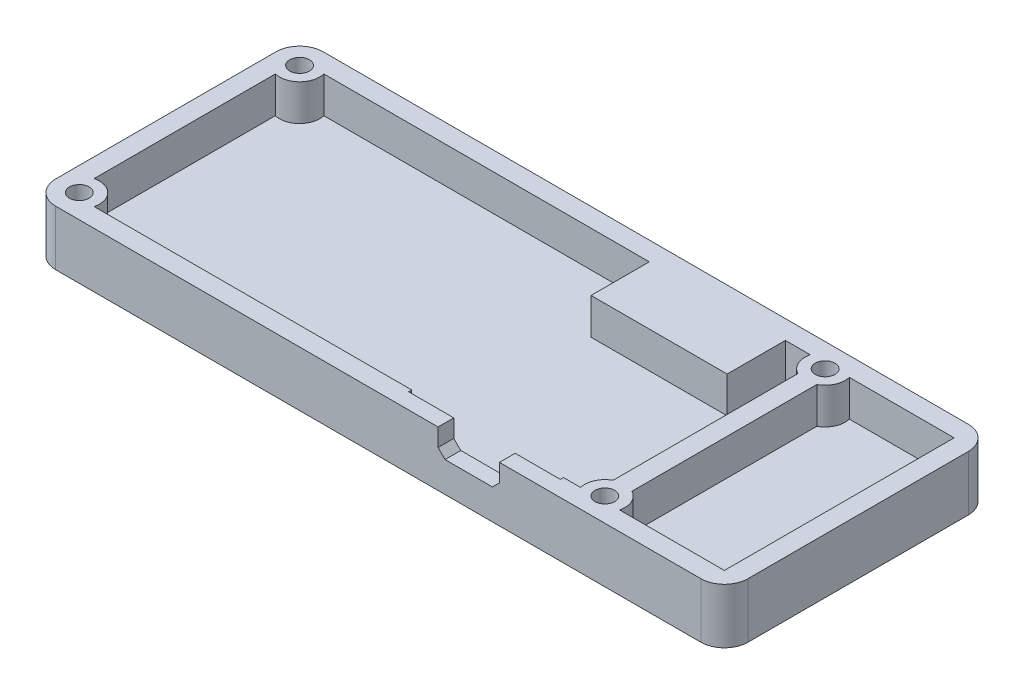
SolidWorks part; units mm, degrees
ref_plane "Front Plane" through (0, 0, 0) normal (0, 0, 1) x (1, 0, 0)
ref_plane "Top Plane" through (0, 0, 0) normal (0, 1, 0) x (1, 0, 0)
ref_plane "Right Plane" through (0, 0, 0) normal (1, 0, 0) x (0, 0, -1)
sketch "Sketch1" plane through (0, 0, 0) normal (0, 1, 0) x (1, 0, 0)
  line L1 (-35.5, 17) -> (35.5, 17)
  line L2 (-35.5, 17) -> (-35.5, -17)
  line L3 (-35.5, -17) -> (35.5, -17)
  line L4 (35.5, 17) -> (35.5, -17)
  line L5 (-35.5, 17) -> (35.5, -17) construction
  line L6 (-35.5, -17) -> (35.5, 17) construction
  point P0 (0, 0)
  dimension "D1" = 34
  dimension "D2" = 71
extrude "Boss-Extrude1" add sketch "Sketch1" along normal blind 7
shell "Shell1" thickness 2.4
sketch "Sketch3" plane through (0, 0, 0) normal (0, -1, 0) x (1, 0, 0)
  line L0 (35.5, 17) -> (35.5, -17) construction
  line L1 (35.5, 17) -> (52.5, 17)
  line L2 (35.5, 17) -> (35.5, -17)
  line L3 (35.5, -17) -> (52.5, -17)
  line L4 (52.5, 17) -> (52.5, -17)
  line L6 (-35.5, 17) -> (35.5, 17) construction
  line L7 (35.5, -17) -> (-35.5, -17) construction
  dimension "D1" = 17
extrude "Boss-Extrude2" add sketch "Sketch3" against normal up to surface (7 mm away) up to face at (0, 7, 0)
sketch "Sketch4" plane through (0, 7, 0) normal (0, 1, 0) x (1, 0, 0)
  line L3 (35.5, -14.6) -> (50.1, -14.6)
  line L8 (35.5, -14.6) -> (35.5, 14.6)
  line L9 (35.5, 14.6) -> (50.1, 14.6)
  line L10 (50.1, -14.6) -> (50.1, 14.6)
  line L11 (33.1, -14.6) -> (33.1, 14.6) construction
  line L12 (52.5, 17) -> (52.5, -17) construction
  line L13 (52.5, 17) -> (-35.5, 17) construction
  line L14 (-35.5, -17) -> (52.5, -17) construction
  dimension "D1" = 2.4
  dimension "D2" = 2.4
  dimension "D3" = 2.4
  dimension "D4" = 2.4
extrude "Cut-Extrude2" cut sketch "Sketch4" against normal offset from surface (4.6 mm away) 2.4 up to face at (8.5, 0, 0)
sketch "Sketch5" plane through (0, 7, 0) normal (0, 1, 0) x (1, 0, 0)
  line L0 (-33.1, -14.6) -> (33.1, -14.6) construction
  line L1 (29.65, -15) -> (10.35, -15)
  line L2 (29.65, -15) -> (29.65, -14.6)
  line L3 (29.65, -14.6) -> (10.35, -14.6)
  line L4 (10.35, -15) -> (10.35, -14.6)
  line L5 (28.65, -15) -> (28.65, 12.9) construction
  line L6 (11.35, -15) -> (11.35, 12.9) construction
  dimension "D1" = 1
  dimension "D2" = 1
  dimension "D3" = 0.4
extrude "Cut-Extrude3" cut sketch "Sketch5" against normal up to surface (4.6 mm away) up to face at (0, 2.4, 0)
sketch "Sketch6" plane through (0, 0, 17) normal (0, 0, 1) x (1, 0, 0)
  line L30 (16.1, 4.7379) -> (16.9879, 3.85)
  line L31 (16.9879, 3.85) -> (23.0121, 3.85)
  line L32 (23.0121, 3.85) -> (23.9, 4.7379)
  line L33 (23.9, 4.7379) -> (23.9, 6.3)
  line L34 (23.25, 6.95) -> (16.75, 6.95)
  line L35 (16.1, 6.3) -> (16.1, 4.7379)
  line L36 (16.1, 4.7379) -> (16.9879, 3.85)
  line L37 (16.9879, 3.85) -> (23.0121, 3.85)
  line L38 (23.0121, 3.85) -> (23.9, 4.7379)
  line L39 (23.9, 4.7379) -> (23.9, 6.3)
  line L41 (16.1, 6.3) -> (16.1, 4.7379)
  line L42 (23.9, 6.3) -> (23.9, 7)
  line L43 (-35.5, 7) -> (52.5, 7) construction
  line L44 (23.9, 7) -> (16.1, 7)
  line L45 (16.1, 7) -> (16.1, 6.3)
  arc A14 (23.9, 6.3) -> (23.25, 6.95) centre (23.25, 6.3) ccw
  arc A15 (16.75, 6.95) -> (16.1, 6.3) centre (16.75, 6.3) ccw
  dimension "D1" = 0.15
extrude "Cut-Extrude4" cut sketch "Sketch6" against normal up to surface (2 mm away) up to face at (20, 4.7, 15)
sketch "Sketch7" plane through (0, 2.4, 0) normal (0, 1, 0) x (1, 0, 0)
  line L0 (33.1, 14.6) -> (-33.1, 14.6) construction
  line L1 (28.65, 14.6) -> (11.35, 14.6)
  line L2 (28.65, 14.6) -> (28.65, 7.2)
  line L3 (28.65, 7.2) -> (11.35, 7.2)
  line L4 (11.35, 14.6) -> (11.35, 7.2)
  line L6 (28.65, -15) -> (28.65, 12.9) construction
  line L7 (11.35, -15) -> (11.35, 12.9) construction
  line L8 (29.65, -15) -> (10.35, -15) construction
  dimension "D1" = 22.2
extrude "Boss-Extrude3" add sketch "Sketch7" along normal up to surface (4.6 mm away) up to face at (12.125, 7, 7.7)
fillet "Fillet1" radius 3 4 edges at (52.5, 3.5, 17) (52.5, 3.5, -17) (-35.5, 3.5, -17) (-35.5, 3.5, 17)
sketch "Sketch8" plane through (0, 0, 0) normal (0, -1, 0) x (-1, 0, 0)
  circle A0 centre (32.5, 14) radius 2.5547
  circle A1 centre (32.5, -14) radius 2.5547
  circle A2 centre (-34.3, 14) radius 2.5547
  circle A3 centre (-34.3, -14) radius 2.5547
  arc A4 (-35.5, -11.7447) -> (-36.7832, -14.6) centre (-34.3, -14) ccw construction
  arc A5 (-36.7832, 14.6) -> (-35.5, 11.7447) centre (-34.3, 14) ccw construction
  arc A6 (33.1, -11.5168) -> (30.0168, -14.6) centre (32.5, -14) ccw construction
  arc A7 (30.0168, 14.6) -> (33.1, 11.5168) centre (32.5, 14) ccw construction
extrude "Boss-Extrude4" add sketch "Sketch8" against normal up to vertex (7 mm away)
sketch "Sketch9" plane through (0, 0, 0) normal (0, -1, 0) x (1, 0, 0)
  circle A0 centre (-32.5, -14) radius 1.25
  circle A1 centre (-32.5, 14) radius 1.25
  circle A2 centre (34.3, -14) radius 1.25
  circle A3 centre (34.3, 14) radius 1.25
  circle A5 centre (-32.5, -14) radius 1.25 construction
  circle A6 centre (-32.5, 14) radius 1.25 construction
  circle A7 centre (34.3, -14) radius 1.25 construction
  circle A8 centre (34.3, 14) radius 1.25 construction
extrude "Cut-Extrude5" cut sketch "Sketch9" against normal up to next
sketch "Sketch10" plane through (0, 0, 0) normal (0, -1, 0) x (1, 0, 0)
  circle A0 centre (34.3, 14) radius 2.15
  circle A1 centre (-32.5, -14) radius 2.15
  circle A2 centre (-32.5, 14) radius 2.15
  circle A3 centre (34.3, -14) radius 2.15
  circle A5 centre (-32.5, 14) radius 1.25 construction
  circle A6 centre (-32.5, -14) radius 1.25 construction
  circle A7 centre (34.3, -14) radius 1.25 construction
  circle A8 centre (34.3, 14) radius 1.25 construction
  dimension "D1" = 4.3
extrude "Cut-Extrude6" cut sketch "Sketch10" against normal blind 1.6
